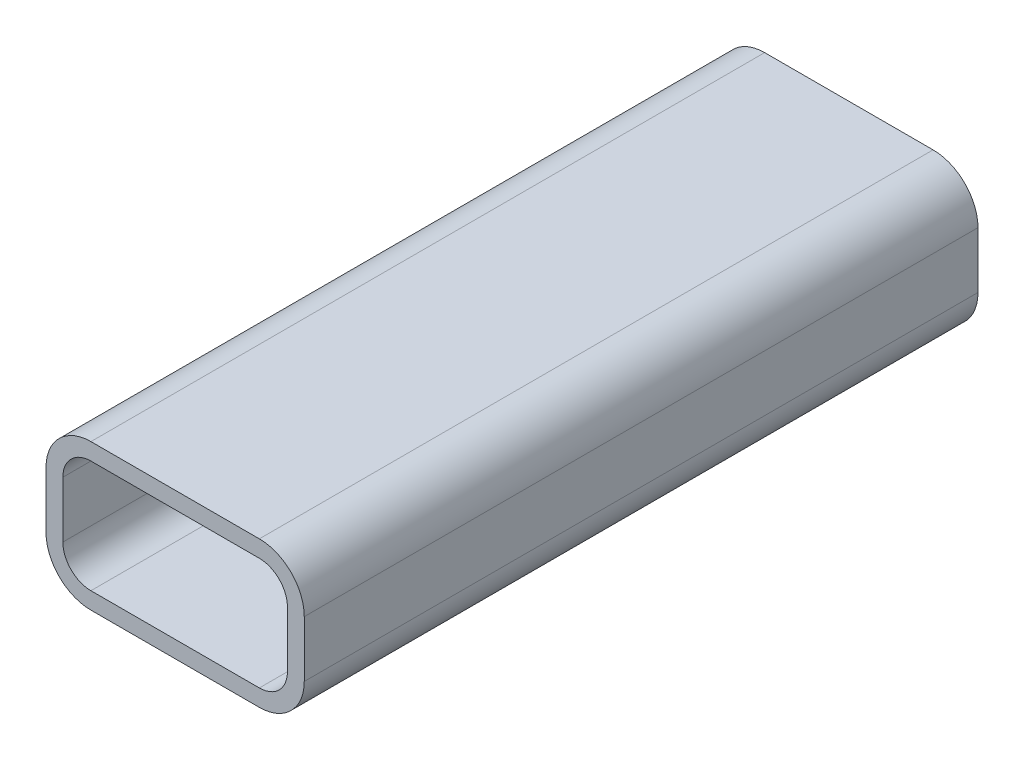
SolidWorks part; units mm, degrees
ref_plane "Front Plane" through (0, 0, 0) normal (0, 0, 1) x (1, 0, 0)
ref_plane "Top Plane" through (0, 0, 0) normal (0, 1, 0) x (1, 0, 0)
ref_plane "Right Plane" through (0, 0, 0) normal (1, 0, 0) x (0, 0, -1)
sketch "Sketch1" plane through (0, 0, 0) normal (0, 0, 1) x (1, 0, 0)
  line L1 (15, 10) -> (-15, 10)
  line L2 (20, 5) -> (20, -5)
  line L3 (15, -10) -> (-15, -10)
  line L4 (-20, 5) -> (-20, -5)
  line L5 (20, 10) -> (-20, -10) construction
  line L6 (20, -10) -> (-20, 10) construction
  arc A0 (15, -10) -> (20, -5) centre (15, -5) ccw
  arc A1 (-20, -5) -> (-15, -10) centre (-15, -5) ccw
  arc A2 (-20, 5) -> (-15, 10) centre (-15, 5) cw
  arc A3 (20, 5) -> (15, 10) centre (15, 5) ccw
  point P0 (0, 0)
  dimension "D3" = 5
  dimension "Width" = 40
  dimension "Height" = 20
extrude "Extrude-Thin1" add sketch "Sketch1" along normal mid plane 120 thin
sketch "Sketch2" plane through (0, 13, 0) normal (0, 1, 0) x (1, 0, 0)
  line L0 (0, 45) -> (0, -45) construction
  line L1 (6, 45) -> (6, -45)
  line L2 (-6, 45) -> (-6, -45)
  line L3 (15, -60) -> (-15, -60) construction
  arc A0 (6, 45) -> (-6, 45) centre (0, 45) ccw
  arc A1 (-6, -45) -> (6, -45) centre (0, -45) ccw
  point P3 (0, 0)
  dimension "D2" = 6
  dimension "D3" = 15
  dimension "D1" = 90
extrude "Cut-Extrude1" [suppressed] cut sketch "Sketch2" against normal through all
